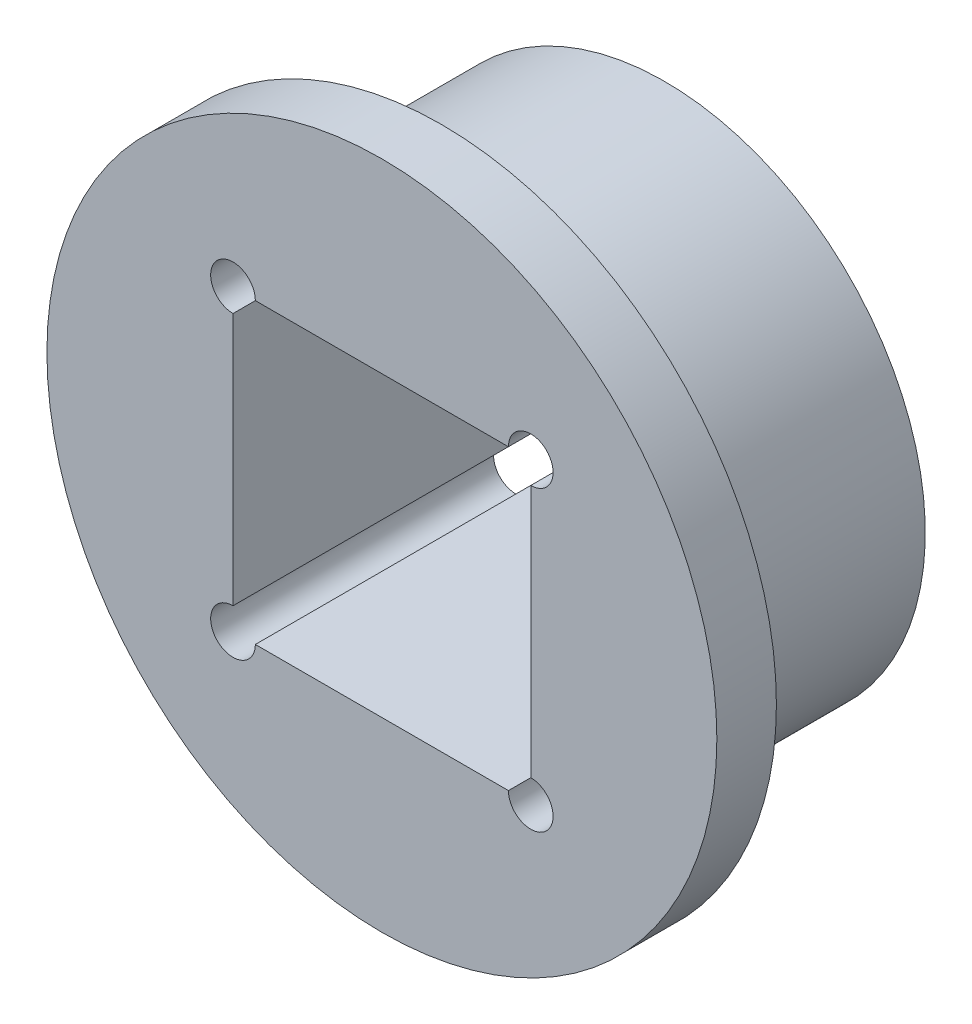
SolidWorks part; units mm, degrees
ref_plane "前视基准面" through (0, 0, 0) normal (0, 0, 1) x (1, 0, 0)
ref_plane "上视基准面" through (0, 0, 0) normal (0, 1, 0) x (1, 0, 0)
ref_plane "右视基准面" through (0, 0, 0) normal (1, 0, 0) x (0, 0, -1)
other "Configuration Table"
sketch "草图1" plane through (0, 0, 0) normal (0, 0, 1) x (1, 0, 0)
  circle A0 centre (0, 0) radius 22.5
  dimension "D1" = 45
extrude "凸台-拉伸1" add sketch "草图1" along normal blind 4
sketch "草图2" plane through (0, 0, 0) normal (0, 0, -1) x (-1, 0, 0)
  circle A0 centre (0, 0) radius 17.5
  dimension "D1" = 35
extrude "凸台-拉伸2" add sketch "草图2" along normal blind 15
sketch "草图3" plane through (0, 0, 4) normal (0, 0, 1) x (1, 0, 0)
  line L1 (-10, 10) -> (10, 10)
  line L2 (-10, 10) -> (-10, -10)
  line L3 (-10, -10) -> (10, -10)
  line L4 (10, 10) -> (10, -10)
  line L5 (-10, 10) -> (10, -10) construction
  line L6 (-10, -10) -> (10, 10) construction
  circle A0 centre (-10, 10) radius 1.5
  circle A1 centre (10, 10) radius 1.5
  circle A2 centre (10, -10) radius 1.5
  circle A3 centre (-10, -10) radius 1.5
  point P0 (0, 0)
  dimension "D2" = 3
  dimension "D3" = 3
  dimension "D4" = 3
  dimension "D5" = 3
  dimension "D1" = 20
extrude "切除-拉伸1" cut sketch "草图3" against normal through all contours L2 A3 L3 | L3 A3 L2 | A3 L3 A2 L4 A1 L1 A0 L2 | L3 A2 L4 | L4 A2 L3 | L4 A1 L1 | L1 A1 L4 | L2 A0 L1 | L1 A0 L2
